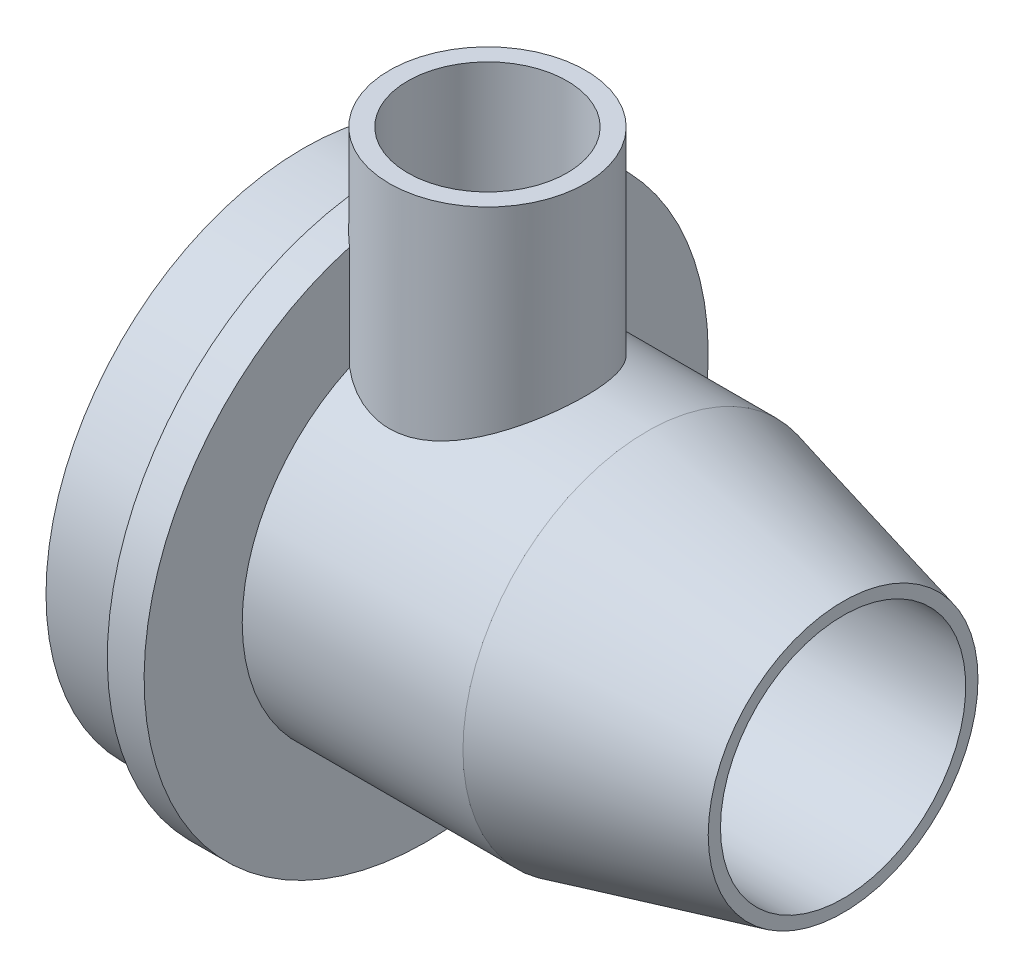
SolidWorks part; units mm, degrees
ref_plane "Plan de face" through (0, 0, 0) normal (0, 0, 1) x (1, 0, 0)
ref_plane "Plan de dessus" through (0, 0, 0) normal (0, 1, 0) x (1, 0, 0)
ref_plane "Plan de droite" through (0, 0, 0) normal (1, 0, 0) x (0, 0, -1)
sketch "Esquisse1" plane through (0, 0, 0) normal (0, 0, 1) x (1, 0, 0)
  line L0 (0, 0) -> (440, 0) construction
  line L1 (0, 100) -> (440, 100)
  line L3 (280, 150) -> (100, 150)
  line L4 (100, 150) -> (100, 230)
  line L5 (100, 230) -> (70, 230)
  line L6 (70, 230) -> (70, 210)
  line L7 (70, 210) -> (0, 210)
  line L8 (0, 210) -> (0, 100)
  line L9 (280, 150) -> (440, 110)
  line L10 (440, 110) -> (440, 100)
  point P12 (0, 0)
  point P13 (0, 0)
  dimension "D1" = 110
  dimension "D2" = 70
  dimension "D3" = 30
  dimension "D4" = 160
  dimension "D5" = 50
  dimension "D6" = 10
  dimension "D7" = 100
  dimension "D8" = 20
  dimension "D9" = 440
revolve "Révolution1" add sketch "Esquisse1" angle 360 about L0
ref_plane "Plan1" through (0, 300, 0) normal (0, 1, 0) x (1, 0, 0)
sketch "Esquisse3" plane through (0, 300, 0) normal (0, 1, 0) x (1, 0, 0)
  line L0 (0, 0) -> (150, 0) construction
  circle A0 centre (150, 0) radius 80
  dimension "D2" = 160
  dimension "D1" = 150
extrude "Boss.-Extru.1" add sketch "Esquisse3" against normal up to body separate body
sketch "Esquisse4" plane through (0, 300, 0) normal (0, 1, 0) x (1, 0, 0)
  circle A0 centre (150, 0) radius 65
  dimension "D1" = 130
extrude "Enlèv. mat.-Extru.1" cut sketch "Esquisse4" against normal blind 280
